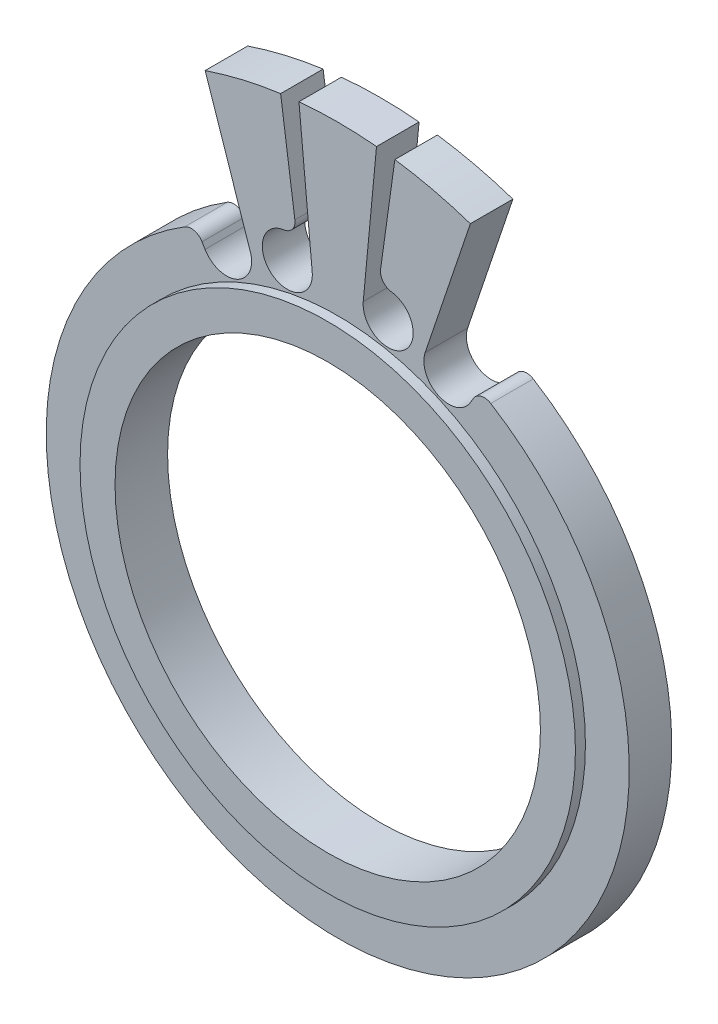
SolidWorks part; units mm, degrees
ref_plane "Plan de face" through (0, 0, 0) normal (0, 0, 1) x (1, 0, 0)
ref_plane "Plan de dessus" through (0, 0, 0) normal (0, 1, 0) x (1, 0, 0)
ref_plane "Plan de droite" through (0, 0, 0) normal (1, 0, 0) x (0, 0, -1)
sketch "Esquisse1" plane through (0, 0, 0) normal (0, 0, 1) x (1, 0, 0)
  line L0 (0, 0) -> (0, 36.3015) construction
  line L1 (0, 0) -> (10.6, 31.4624) construction
  line L2 (0, 0) -> (4.5653, 32.8846) construction
  line L3 (10.6048, 19.0853) -> (10.8446, 19.4904)
  line L4 (10.6, 31.4624) -> (6.9884, 20.7426)
  line L5 (0, 0) -> (0, -28.9341) construction
  line L6 (2.039, 21.793) -> (3.1, 33.055)
  line L7 (-10.6048, 19.0853) -> (-10.8446, 19.4904)
  line L8 (3.426, 24.7186) -> (4.5653, 32.8846)
  line L9 (-10.6, 31.4624) -> (-6.9884, 20.7426)
  line L10 (-3.426, 24.7186) -> (-4.5653, 32.8846)
  line L11 (-2.039, 21.793) -> (-3.1, 33.055)
  circle A0 centre (0, 0) radius 17
  arc A1 (-12.23, 19.8322) -> (12.23, 19.8322) centre (0, 0) ccw
  arc A2 (10.6, 31.4624) -> (4.5653, 32.8846) centre (0, 0) ccw
  arc A3 (3.1, 33.055) -> (-3.1, 33.055) centre (0, 0) ccw
  arc A4 (-10.8446, 19.4904) -> (-12.23, 19.8322) centre (-11.7051, 18.981) ccw
  arc A5 (6.9884, 20.7426) -> (10.6048, 19.0853) centre (8.8837, 20.104) ccw
  arc A6 (2.039, 21.793) -> (4.2877, 23.5888) centre (4.0302, 21.6054) ccw
  arc A7 (10.8446, 19.4904) -> (12.23, 19.8322) centre (11.7051, 18.981) cw
  arc A8 (3.426, 24.7186) -> (4.2877, 23.5888) centre (4.4164, 24.5805) ccw
  arc A9 (-6.9884, 20.7426) -> (-10.6048, 19.0853) centre (-8.8837, 20.104) cw
  arc A10 (-10.6, 31.4624) -> (-4.5653, 32.8846) centre (0, 0) cw
  arc A11 (-3.426, 24.7186) -> (-4.2877, 23.5888) centre (-4.4164, 24.5805) cw
  arc A12 (-2.039, 21.793) -> (-4.2877, 23.5888) centre (-4.0302, 21.6054) cw
  dimension "D1" = 34
  dimension "D2" = 46.6
  dimension "D3" = 66.4
  dimension "D8" = 4
  dimension "D9" = 4
  dimension "D10" = 1
  dimension "D11" = 1
  dimension "D6" = 6.2
extrude "Boss.-Extru.1" add sketch "Esquisse1" along normal blind 3.4
sketch "Esquisse2" plane through (0, 0, 3.4) normal (0, 0, 1) x (1, 0, 0)
  circle A0 centre (0, 0) radius 17 construction
  circle A1 centre (0, 0) radius 17
  circle A2 centre (0, 0) radius 19.8
  dimension "D1" = 39.6
extrude "Boss.-Extru.2" add sketch "Esquisse2" along normal blind 0.8
